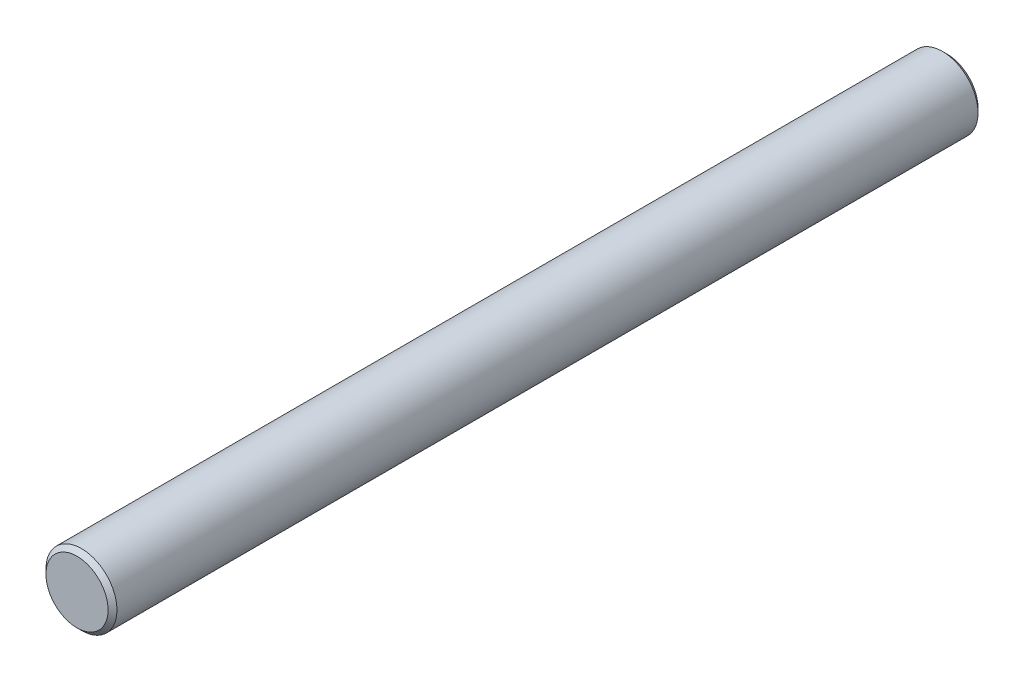
SolidWorks part; units mm, degrees
material "Plain Carbon Steel"
ref_plane "Front Plane" through (0, 0, 0) normal (0, 0, 1) x (1, 0, 0)
ref_plane "Top Plane" through (0, 0, 0) normal (0, 1, 0) x (1, 0, 0)
ref_plane "Right Plane" through (0, 0, 0) normal (1, 0, 0) x (0, 0, -1)
sketch "Sketch1" plane through (0, 0, 0) normal (0, 0, 1) x (1, 0, 0)
  circle A0 centre (0, 0) radius 4
  dimension "D1" = 8
extrude "Boss-Extrude1" add sketch "Sketch1" along normal blind 98
chamfer "Chamfer1" distance 0.5 angle 45 2 edges at (4, 0, 0) (4, 0, 98)
